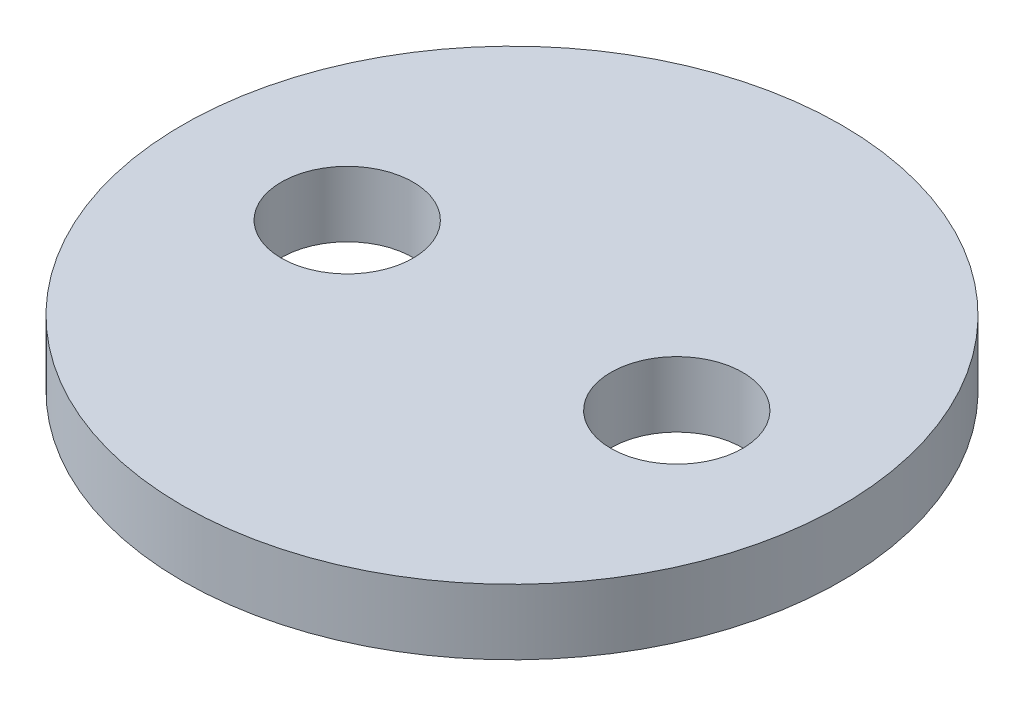
SolidWorks part; units mm, degrees
ref_plane "Front Plane" through (0, 0, 0) normal (0, 0, 1) x (1, 0, 0)
ref_plane "Top Plane" through (0, 0, 0) normal (0, 1, 0) x (1, 0, 0)
ref_plane "Right Plane" through (0, 0, 0) normal (1, 0, 0) x (0, 0, -1)
sketch "Sketch1" plane through (0, 0, 0) normal (0, 1, 0) x (1, 0, 0)
  line L0 (0, 0) -> (16, 0) construction
  line L1 (0, 0) -> (-16, 0) construction
  circle A0 centre (0, 0) radius 16
  circle A1 centre (8, 0) radius 3.2
  circle A2 centre (-8, 0) radius 3.2
  dimension "D1" = 32
  dimension "D2" = 6.4
  dimension "D3" = 6.4
extrude "Boss-Extrude3" add sketch "Sketch1" along normal blind 3.175
